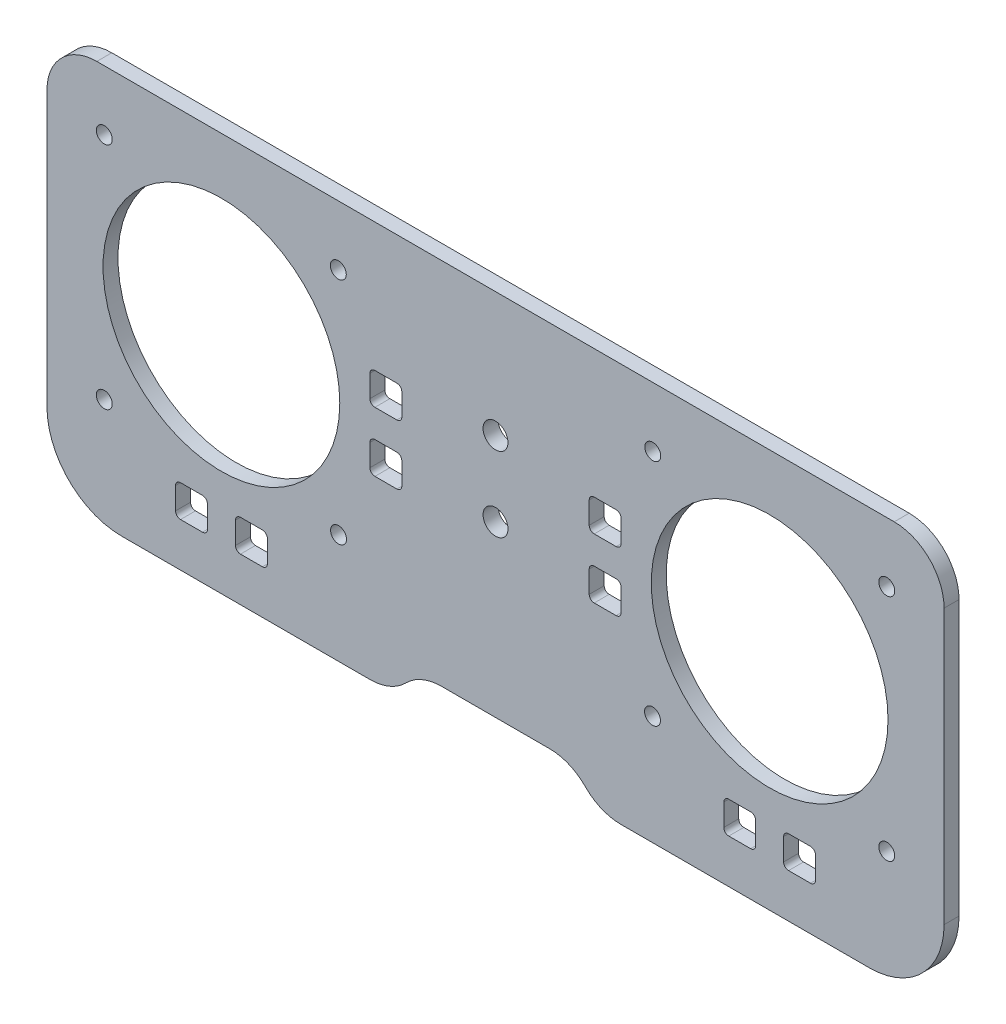
SolidWorks part; units mm, degrees
material "Acrylic (Medium-high impact)"
ref_plane "Front Plane" through (0, 0, 0) normal (0, 0, 1) x (1, 0, 0)
ref_plane "Top Plane" through (0, 0, 0) normal (0, 1, 0) x (1, 0, 0)
ref_plane "Right Plane" through (0, 0, 0) normal (1, 0, 0) x (0, 0, -1)
sketch "Sketch1" plane through (0, 0, 0) normal (0, 0, 1) x (1, 0, 0)
  line L0 (0, 40) -> (0, -40) construction
  line L1 (-90, 40) -> (90, 40)
  line L2 (-90, 40) -> (-90, -40)
  line L3 (-90, -40) -> (90, -40)
  line L4 (90, 40) -> (90, -40)
  line L5 (90, 0) -> (-90, 0) construction
  line L6 (90, 5) -> (-90, 5) construction
  line L7 (-90, 5) -> (-55, 5) construction
  line L8 (90, 5) -> (55, 5) construction
  circle A0 centre (55, 5) radius 23.75
  circle A1 centre (-55, 5) radius 23.75
  point P8 (0, 0)
extrude "Boss-Extrude1" add sketch "Sketch1" along normal blind 3
sketch "Sketch2" plane through (0, 0, 3) normal (0, 0, 1) x (1, 0, 0)
  line L0 (-55, 5) -> (-55, -49995) construction
  line L1 (-55, 5) -> (49945, 5) construction
  line L2 (55, 5) -> (55, -49995) construction
  line L3 (-25, 5) -> (-25, -49995) construction
  line L4 (25, 5) -> (25, -49995) construction
  line L5 (-55, -25) -> (49945, -25) construction
  line L6 (-55, -31) -> (49945, -31) construction
  line L7 (-19, 5) -> (-19, -49995) construction
  line L8 (19, 5) -> (19, -49995) construction
  line L9 (-55, 2) -> (49945, 2) construction
  line L10 (-55, 8) -> (49945, 8) construction
  line L11 (-55, -4) -> (49945, -4) construction
  line L12 (-55, 14) -> (49945, 14) construction
  line L13 (-58, 5) -> (-58, -49995) construction
  line L14 (52, 5) -> (52, -49995) construction
  line L15 (-52, 5) -> (-52, -49995) construction
  line L16 (58, 5) -> (58, -49995) construction
  line L17 (-64, 5) -> (-64, -49995) construction
  line L18 (46, 5) -> (46, -49995) construction
  line L19 (-46, 5) -> (-46, -49995) construction
  line L20 (64, 5) -> (64, -49995) construction
  line L21 (-64.2, -24.8) -> (-64.2, -31.2)
  line L22 (-25, 14) -> (-19, 14) construction
  line L23 (-25, 14) -> (-25, 8) construction
  line L24 (-25, 8) -> (-19, 8) construction
  line L25 (-19, 14) -> (-19, 8) construction
  line L26 (-25, 2) -> (-19, 2) construction
  line L27 (-25, 2) -> (-25, -4) construction
  line L28 (-25, -4) -> (-19, -4) construction
  line L29 (-19, 2) -> (-19, -4) construction
  line L30 (-64, -25) -> (-58, -25) construction
  line L31 (-64, -25) -> (-64, -31) construction
  line L32 (-64, -31) -> (-58, -31) construction
  line L33 (-58, -25) -> (-58, -31) construction
  line L34 (-51.9776, -25) -> (-45.9751, -25) construction
  line L35 (-51.9776, -25) -> (-51.9776, -31) construction
  line L36 (-51.9776, -31) -> (-45.9751, -31) construction
  line L37 (-45.9751, -25) -> (-45.9751, -31) construction
  line L38 (46, -25) -> (52, -25) construction
  line L39 (46, -25) -> (46, -31) construction
  line L40 (46, -31) -> (52, -31) construction
  line L41 (52, -25) -> (52, -31) construction
  line L42 (58, -25) -> (64, -25) construction
  line L43 (58, -25) -> (58, -31) construction
  line L44 (58, -31) -> (64, -31) construction
  line L45 (64, -25) -> (64, -31) construction
  line L46 (19, 14) -> (25, 14) construction
  line L47 (19, 14) -> (19, 8) construction
  line L48 (19, 8) -> (25, 8) construction
  line L49 (25, 14) -> (25, 8) construction
  line L50 (19, 2) -> (25, 2) construction
  line L51 (19, 2) -> (19, -4) construction
  line L52 (19, -4) -> (25, -4) construction
  line L53 (25, 2) -> (25, -4) construction
  line L54 (-64.2, -31.2) -> (-57.8, -31.2)
  line L55 (-57.8, -24.8) -> (-57.8, -31.2)
  line L56 (-64.2, -24.8) -> (-57.8, -24.8)
  line L57 (-52.1776, -24.8) -> (-45.7751, -24.8)
  line L58 (-45.7751, -24.8) -> (-45.7751, -31.2)
  line L59 (-52.1776, -31.2) -> (-45.7751, -31.2)
  line L60 (-52.1776, -24.8) -> (-52.1776, -31.2)
  line L61 (-25.2, -4.2) -> (-18.8, -4.2)
  line L62 (-18.8, 2.2) -> (-18.8, -4.2)
  line L63 (-25.2, 2.2) -> (-18.8, 2.2)
  line L64 (-25.2, 2.2) -> (-25.2, -4.2)
  line L65 (-25.2, 7.8) -> (-18.8, 7.8)
  line L66 (-18.8, 14.2) -> (-18.8, 7.8)
  line L67 (-25.2, 14.2) -> (-18.8, 14.2)
  line L68 (-25.2, 14.2) -> (-25.2, 7.8)
  line L69 (18.8, 2.2) -> (25.2, 2.2)
  line L70 (25.2, 2.2) -> (25.2, -4.2)
  line L71 (18.8, -4.2) -> (25.2, -4.2)
  line L72 (18.8, 2.2) -> (18.8, -4.2)
  line L73 (18.8, 7.8) -> (25.2, 7.8)
  line L74 (25.2, 14.2) -> (25.2, 7.8)
  line L75 (18.8, 14.2) -> (25.2, 14.2)
  line L76 (18.8, 14.2) -> (18.8, 7.8)
  line L77 (45.8, -31.2) -> (52.2, -31.2)
  line L78 (52.2, -24.8) -> (52.2, -31.2)
  line L79 (45.8, -24.8) -> (52.2, -24.8)
  line L80 (45.8, -24.8) -> (45.8, -31.2)
  line L81 (57.8, -31.2) -> (64.2, -31.2)
  line L82 (64.2, -24.8) -> (64.2, -31.2)
  line L83 (57.8, -24.8) -> (64.2, -24.8)
  line L84 (57.8, -24.8) -> (57.8, -31.2)
extrude "Cut-Extrude1" cut sketch "Sketch2" against normal through all
sketch "Sketch3" plane through (0, 0, 3) normal (0, 0, 1) x (1, 0, 0)
  line L0 (0, 40) -> (0, -40) construction
  line L1 (90, 40) -> (-90, 40) construction
  line L2 (-90, -40) -> (90, -40) construction
  line L3 (0, -40) -> (0, -34) construction
  line L4 (0, -34) -> (15, -34) construction
  line L5 (0, -34) -> (-15, -34) construction
  line L6 (-15, -34) -> (-15, -40) construction
  line L7 (-15, -40) -> (-21, -40) construction
  line L8 (-21, -40) -> (-15, -34) construction
  line L9 (15, -34) -> (15, -40) construction
  line L10 (15, -40) -> (21, -40) construction
  line L11 (21, -40) -> (15, -34) construction
  line L12 (-21, -40) -> (-15, -34)
  line L13 (-15, -34) -> (15, -34)
  line L14 (15, -34) -> (21, -40)
  line L15 (21, -40) -> (-21, -40)
extrude "Cut-Extrude2" cut sketch "Sketch3" against normal blind 3
sketch "Sketch4" plane through (0, 0, 3) normal (0, 0, 1) x (1, 0, 0)
  line L0 (-55, -18) -> (49945, -18) construction
  line L1 (-55, 28) -> (49945, 28) construction
  line L2 (0, 0) -> (0, -50000) construction
  line L3 (-55, -18.75) -> (-55, 49981.25) construction
  line L4 (-31.5, -18.75) -> (-31.5, 49981.25) construction
  line L5 (-78.5, -18.75) -> (-78.5, 49981.25) construction
  line L6 (-55, 5) -> (49945, 5) construction
  circle A0 centre (-78.5, 28) radius 1.6
  circle A1 centre (-31.5459, 28) radius 1.6
  circle A2 centre (-31.5, -18) radius 1.6
  circle A3 centre (-78.5, -18) radius 1.6
  circle A4 centre (31.5, -18) radius 1.6
  circle A5 centre (31.5459, 28) radius 1.6
  circle A6 centre (78.5, 28) radius 1.6
  circle A7 centre (78.5, -18) radius 1.6
extrude "Cut-Extrude3" cut sketch "Sketch4" against normal blind 3
sketch "Sketch7" plane through (0, 0, 3) normal (0, 0, 1) x (1, 0, 0)
  line L0 (0, 0) -> (0, -50000) construction
  line L1 (0, 0) -> (0, 15) construction
  circle A0 centre (0, 0) radius 2.5
  circle A1 centre (0, 15) radius 2.5
extrude "Cut-Extrude4" cut sketch "Sketch7" against normal blind 3
fillet "Fillet1" radius 10 2 edges at (90, 40, 1.5) (-90, 40, 1.5)
fillet "Fillet2" radius 15 2 edges at (90, -40, 1.5) (-90, -40, 1.5)
fillet "Fillet3" radius 10 4 edges at (21, -40, 1.5) (15, -34, 1.5) (-15, -34, 1.5) (-21, -40, 1.5)
fillet "Fillet4" radius 1 32 edges at (-57.8, -31.2, 1.5) (-64.2, -24.8, 1.5) (-57.8, -24.8, 1.5) (-45.7751, -24.8, 1.5) (-45.7751, -31.2, 1.5) (-52.1776, -31.2, 1.5) (-52.1776, -24.8, 1.5) (-18.8, 2.2, 1.5) (-18.8, -4.2, 1.5) (-25.2, -4.2, 1.5) (-25.2, 2.2, 1.5) (-18.8, 14.2, 1.5) (-18.8, 7.8, 1.5) (-25.2, 7.8, 1.5) (-25.2, 14.2, 1.5) (25.2, 2.2, 1.5) (25.2, -4.2, 1.5) (18.8, -4.2, 1.5) (18.8, 2.2, 1.5) (25.2, 14.2, 1.5) (25.2, 7.8, 1.5) (18.8, 7.8, 1.5) (18.8, 14.2, 1.5) (52.2, -24.8, 1.5) (52.2, -31.2, 1.5) (45.8, -31.2, 1.5) (45.8, -24.8, 1.5) (64.2, -24.8, 1.5) (64.2, -31.2, 1.5) (57.8, -31.2, 1.5) (57.8, -24.8, 1.5) (-64.2, -31.2, 1.5)
